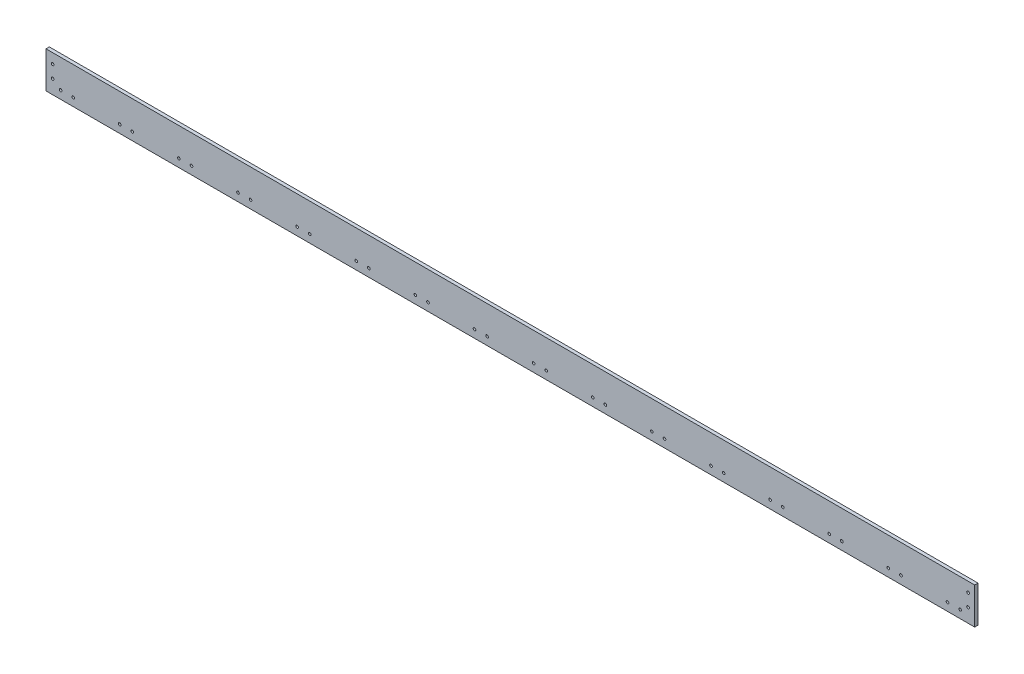
SolidWorks part; units mm, degrees
ref_plane "Front Plane" through (0, 0, 0) normal (0, 0, 1) x (1, 0, 0)
ref_plane "Top Plane" through (0, 0, 0) normal (0, 1, 0) x (1, 0, 0)
ref_plane "Right Plane" through (0, 0, 0) normal (1, 0, 0) x (0, 0, -1)
sketch "Sketch1" plane through (0, 0, 0) normal (0, 0, 1) x (1, 0, 0)
  line L1 (0, 0) -> (1778, 0)
  line L2 (0, 0) -> (0, 69.85)
  line L3 (0, 69.85) -> (1778, 69.85)
  line L4 (1778, 0) -> (1778, 69.85)
  dimension "D1" = 69.85
  dimension "D2" = 1778
extrude "Boss-Extrude1" add sketch "Sketch1" along normal blind 6.35
sketch "Sketch2" plane through (0, 0, 6.35) normal (0, 0, 1) x (1, 0, 0)
  line L0 (27.94, 0) -> (27.94, 12.7) construction
  line L2 (0, 15.24) -> (25.4, 15.24) construction
  line L3 (0, 69.85) -> (0, 0) construction
  line L4 (0, 0) -> (1778, 0) construction
  line L5 (30.48, 15.24) -> (49.53, 15.24) construction
  circle A0 centre (27.94, 15.24) radius 2.54
  circle A1 centre (52.07, 15.24) radius 2.54
  point P13 (1219.2, 76.2)
  dimension "D2" = 5.08
  dimension "D1" = 5.08
  dimension "D3" = 19.05
  dimension "D5" = 12.7
  dimension "D4" = 25.4
extrude "Cut-Extrude1" cut sketch "Sketch2" against normal up to surface (6.35 mm away) contours A1 | A0 up to face at (889, 34.925, 0)
sketch "Sketch3" plane through (0, 0, 6.35) normal (0, 0, 1) x (1, 0, 0)
  line L0 (0, 69.85) -> (0, 0) construction
  line L1 (1778, 69.85) -> (0, 69.85) construction
  line L2 (12.7, 38.735) -> (0, 38.735) construction
  line L3 (12.7, 48.26) -> (12.7, 29.21) construction
  line L4 (0, 38.735) -> (0, 34.925) construction
  line L5 (889, 69.85) -> (889, 0) construction
  line L6 (0, 0) -> (1778, 0) construction
  circle A0 centre (12.7, 26.67) radius 2.54
  circle A1 centre (12.7, 50.8) radius 2.54
  circle A2 centre (1765.3, 26.67) radius 2.54
  circle A3 centre (1765.3, 50.8) radius 2.54
  point P13 (0, 34.925)
  point P15 (889, 69.85)
  point P17 (12.7, 38.735)
  point P27 (12.7, 38.735)
  dimension "D2" = 5.08
  dimension "D1" = 5.08
  dimension "D3" = 19.05
  dimension "D4" = 12.7
  dimension "D5" = 3.81
extrude "Cut-Extrude2" cut sketch "Sketch3" against normal up to surface (6.35 mm away) up to face at (25.4, 15.24, 0)
pattern_linear "LPattern2" count 16 spacing 113.1993 along (1, 0, 0) of "Cut-Extrude1"
equation "\"vertical-component-width\"= 70in'= \"railing-hypotenuse\" - \"railing-hypotenuse-vertical-component-width-difference\""
equation "\"vertical-component-height\"= 2.75in"
equation "\"material-thickness\"= .25in"
equation "\"D1@Sketch1\"=\"vertical-component-height\""
equation "\"D2@Sketch1\"=\"vertical-component-width\""
equation "\"D1@Boss-Extrude1\"=\"material-thickness\""
equation "\"mounting-hole-diameter\"= .2"
equation "\"mounting-hole-pair-left-to-mount-edge-left\"= 1in"
equation "\"mounting-hole-bottom-to-mount-edge-bottom\"= .5in"
equation "\"mounting-hole-pair-distance-between-holes\"= .75in"
equation "\"distance-between-mounting-hole-pairs\"= ( \"vertical-component-width\" - 2 * \"mounting-hole-pair-left-to-mount-edge-left\" - \"num-mounting-hole-pairs\" * ( 2 * \"mounting-hole-diameter\" + \"mounting-hole-pair-distance-between-holes\" ) ) / ( \"num-mounting-hole-pairs\" - 1 )"
equation "\"num-mounting-hole-pairs\"= 16"
equation "\"D3@Sketch2\"=\"mounting-hole-pair-distance-between-holes\""
equation "\"D5@Sketch2\"=\"mounting-hole-bottom-to-mount-edge-bottom\""
equation "\"D4@Sketch2\"=\"mounting-hole-pair-left-to-mount-edge-left\""
equation "\"D3@LPattern2\"=\"mounting-hole-pair-left-to-next-mounting-hole-pair-left\""
equation "\"D2@Sketch2\"=\"mounting-hole-diameter\""
equation "\"D1@Sketch2\"=\"mounting-hole-diameter\""
equation "\"mounting-hole-pair-left-to-next-mounting-hole-pair-left\"= \"distance-between-mounting-hole-pairs\" + 2 * \"mounting-hole-diameter\" + \"mounting-hole-pair-distance-between-holes\""
equation "\"edge-mounting-hole-pair-inset\"=0.5"
equation "\"D4@Sketch3\"=\"edge-mounting-hole-pair-inset\""
equation "\"edge-mounting-hole-pair-offset-from-mount-vertical-center\"= 0.15"
equation "\"D5@Sketch3\"=\"edge-mounting-hole-pair-offset-from-mount-vertical-center\""
equation "\"D3@Sketch3\"=\"mounting-hole-pair-distance-between-holes\""
equation "\"railing-hypotenuse\"= 72in"
equation "\"railing-hypotenuse-vertical-component-width-difference\"= 1.75in"
equation "\"D1@LPattern2\"=\"num-mounting-hole-pairs\""
